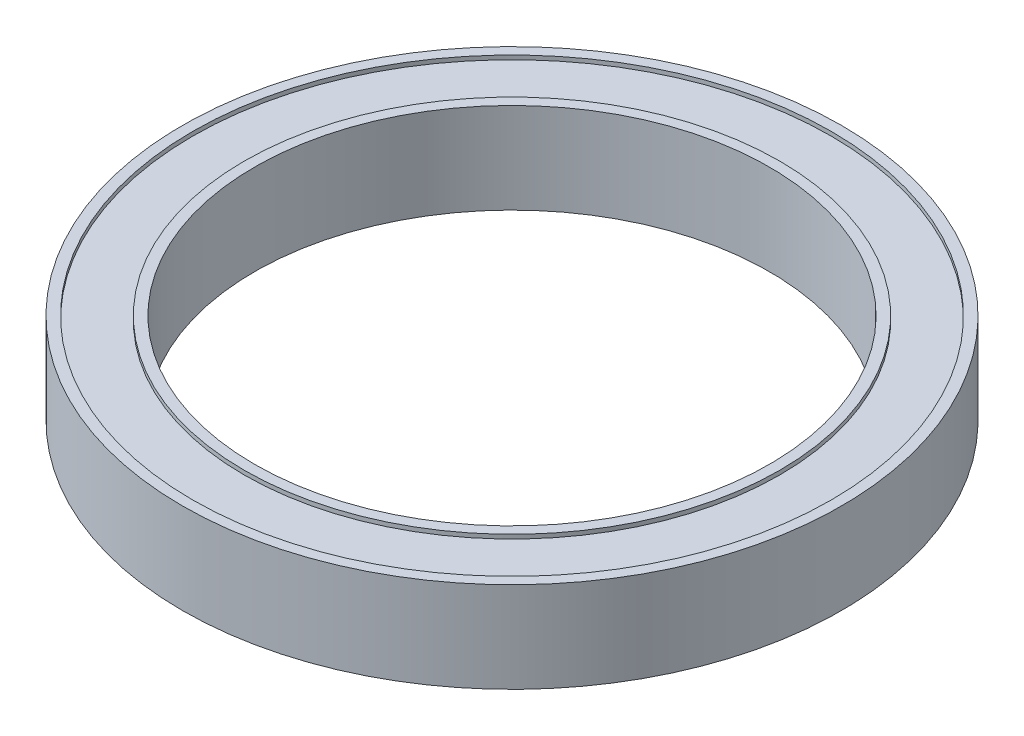
SolidWorks part; units mm, degrees
ref_plane "Front Plane" through (0, 0, 0) normal (0, 0, 1) x (1, 0, 0)
ref_plane "Top Plane" through (0, 0, 0) normal (0, 1, 0) x (1, 0, 0)
ref_plane "Right Plane" through (0, 0, 0) normal (1, 0, 0) x (0, 0, -1)
sketch "Sketch1" plane through (0, 0, 0) normal (0, 1, 0) x (1, 0, 0)
  circle A0 centre (0, 0) radius 12.5
  circle A1 centre (0, 0) radius 16
  dimension "D1" = 32
  dimension "D2" = 25
extrude "Boss-Extrude1" add sketch "Sketch1" along normal blind 4
sketch "Sketch2" plane through (0, 4, 0) normal (0, 1, 0) x (1, 0, 0)
  circle A0 centre (0, 0) radius 12.5
  circle A1 centre (0, 0) radius 12.5 construction
  circle A2 centre (0, 0) radius 16
  circle A3 centre (0, 0) radius 13
  circle A4 centre (0, 0) radius 15.5
  circle A5 centre (0, 0) radius 16 construction
  circle M5 centre (0, 0) radius 16
  circle M6 centre (0, 0) radius 12.5
  dimension "D1" = 0.5
  dimension "D2" = 0.5
extrude "Boss-Extrude2" add sketch "Sketch2" along normal blind 0.2 and the other way offset from surface (4.2 mm away) 0.2 contours A3 M6 | A4 M5 other way up to face at (0, 0, 16)
